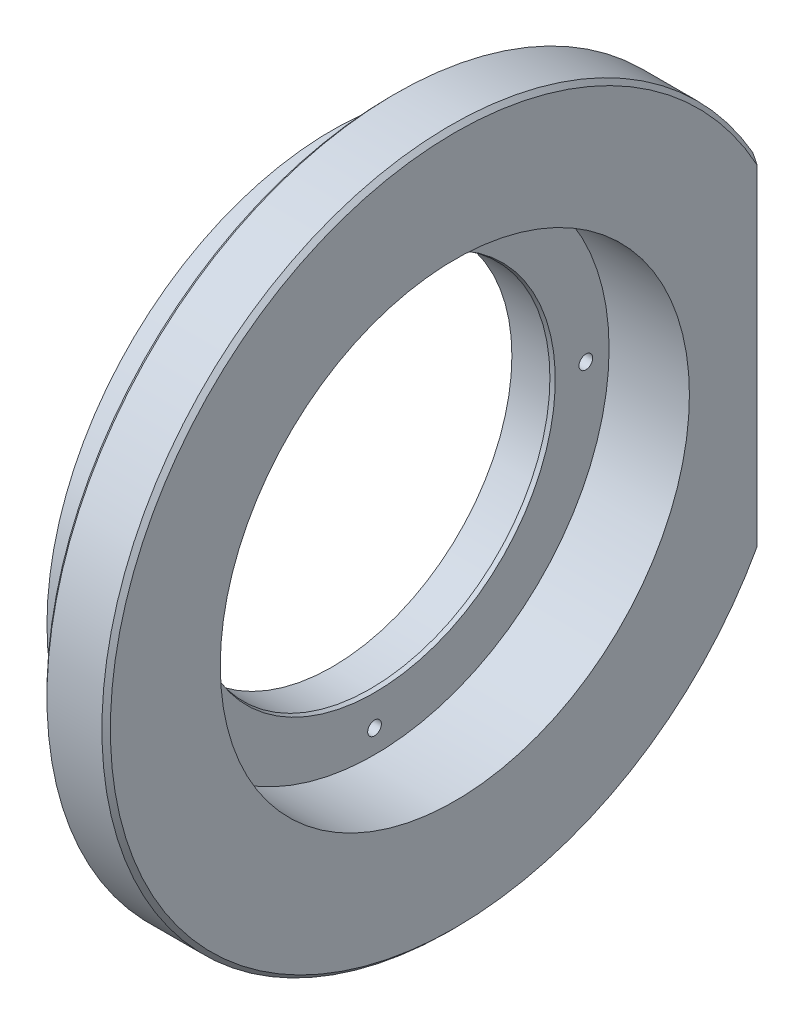
SolidWorks part; units mm, degrees
ref_plane "前基準面" through (0, 0, 0) normal (0, 0, 1) x (1, 0, 0)
ref_plane "上基準面" through (0, 0, 0) normal (0, 1, 0) x (1, 0, 0)
ref_plane "右基準面" through (0, 0, 0) normal (1, 0, 0) x (0, 0, -1)
ref_plane "平面1" through (125, 0, 0) normal (-1, 0, 0) x (0, -1, 0)
sketch "草圖1" plane through (125, 0, 0) normal (-1, 0, 0) x (0, -1, 0)
  line L0 (-41.1582, -71.5) -> (41.1582, -71.5)
  arc A0 (41.1582, -71.5) -> (-41.1582, -71.5) centre (0, 0) ccw
extrude "填料-伸長1" add sketch "草圖1" against normal blind 15
sketch "草圖2" plane through (0, 0, 0) normal (0, 0, 1) x (1, 0, 0)
  line L0 (111, 67.5) -> (111, 0)
  line L1 (111, 0) -> (125, 0)
  line L2 (125, 0) -> (125, 67.5)
  line L3 (125, 67.5) -> (111, 67.5)
  line L4 (111, 0) -> (125, 0) construction
revolve "旋轉1" add sketch "草圖2" angle 360 about L4
hole_wizard "鑽孔1" positions "草圖4" profile "草圖3" legacy
sketch "草圖4" plane through (140, 0, 0) normal (1, 0, 0) x (0, 0, -1)
  point P0 (0, 0)
sketch "草圖3" plane through (140, 0, 0) normal (0, 1, 0) x (0, 0, -1)
  line L0 (0, 0) -> (0, 29)
  line L1 (0, 29) -> (42.5, 29)
  line L2 (42.5, 29) -> (42.5, 19)
  line L3 (42.5, 19) -> (55.5, 19)
  line L4 (55.5, 19) -> (55.5, 0)
  line L5 (55.5, 0) -> (0, 0)
  line L6 (0, 110) -> (0, -10) construction
  dimension "直徑" = 85
  dimension "深度" = 29
  dimension "柱孔直徑1" = 111
  dimension "柱孔深度1" = 19
hole_wizard "鑽孔2" positions "草圖6" profile "草圖5" legacy
sketch "草圖6" plane through (121, 0, 0) normal (1, 0, 0) x (0, 0, -1)
  point P0 (0, 50)
  point P1 (-50, 0)
  point P2 (0, -50)
  point P3 (50, 0)
sketch "草圖5" plane through (121, 50, 0) normal (0, 1, 0) x (0, 0, -1)
  line L0 (0, 0) -> (0, 8.974)
  line L1 (0, 8.974) -> (1.621, 8)
  line L2 (1.621, 8) -> (1.621, 0)
  line L4 (1.621, 0) -> (0, 0)
  line L6 (0, 8.974) -> (-1.621, 8) construction
  line L7 (0, -4.2442) -> (0, 117.3081) construction
  dimension "直徑" = 3.242
  dimension "深度" = 8
  dimension "導頭角度" = 118
chamfer "導角1" distance 1 angle 45 2 edges at (140, 0, 82.5) (125, 0, 82.5)
chamfer "導角2" distance 0.2679 angle 75 1 edges at (121, 0, -42.5)
